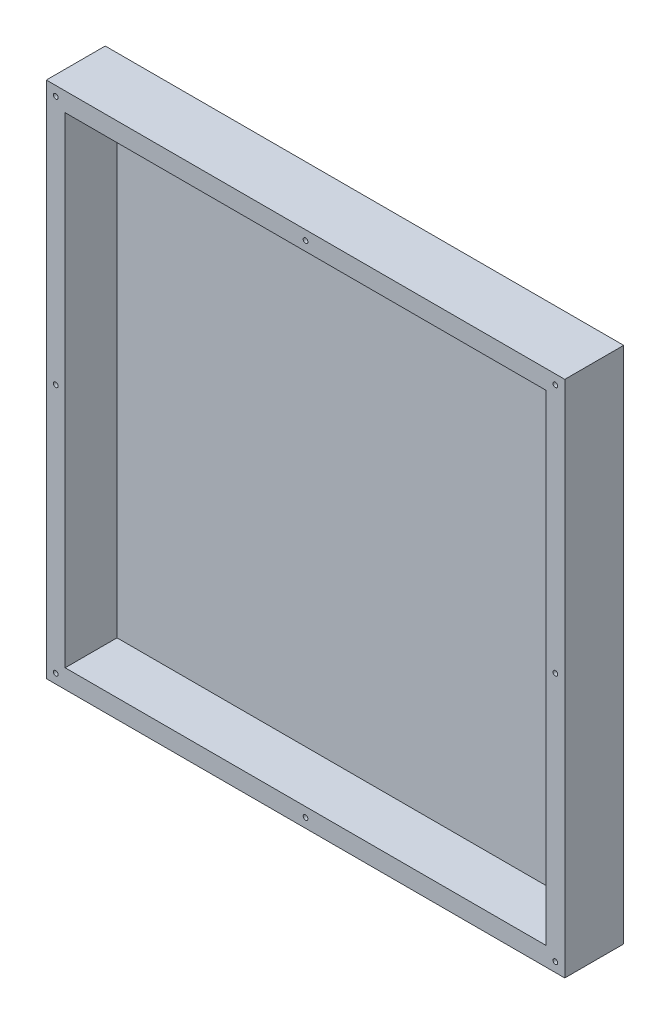
SolidWorks part; units mm, degrees
ref_plane "Front Plane" through (0, 0, 0) normal (0, 0, 1) x (1, 0, 0)
ref_plane "Top Plane" through (0, 0, 0) normal (0, 1, 0) x (1, 0, 0)
ref_plane "Right Plane" through (0, 0, 0) normal (1, 0, 0) x (0, 0, -1)
sketch "Sketch1" plane through (0, 0, 0) normal (0, 0, 1) x (1, 0, 0)
  line L0 (0, 0) -> (220, 0)
  line L1 (55, 0) -> (-55, 0) construction
  line L2 (220, 0) -> (220, 220)
  line L3 (220, 220) -> (0, 220)
  line L4 (0, -55) -> (0, 55) construction
  line L5 (0, 220) -> (0, 0)
extrude "Boss-Extrude1" add sketch "Sketch1" along normal blind 3
sketch "Sketch2" plane through (0, 0, 3) normal (0, 0, 1) x (1, 0, 0)
  line L8 (8, 212) -> (8, 8)
  line L9 (220, 220) -> (0, 220)
  line L10 (220, 220) -> (220, 0)
  line L11 (220, 0) -> (0, 0)
  line L12 (0, 220) -> (0, 0)
  line L13 (212, 8) -> (8, 8)
  line L14 (212, 212) -> (212, 8)
  line L15 (212, 212) -> (8, 212)
  dimension "D1" = 8
extrude "Boss-Extrude3" add sketch "Sketch2" along normal blind 22
sketch "Sketch3" plane through (0, 0, 25) normal (0, 0, 1) x (1, 0, 0)
  line L14 (216, 4) -> (216, 216)
  line L15 (4, 4) -> (216, 4)
  line L16 (4, 216) -> (4, 4)
  line L17 (216, 216) -> (4, 216)
  line L18 (216, 4) -> (216, 216) construction
  line L19 (4, 4) -> (216, 4) construction
  line L20 (4, 216) -> (4, 4) construction
  line L21 (216, 216) -> (4, 216) construction
  circle A0 centre (4, 216) radius 1
  circle A1 centre (110, 216) radius 1
  circle A2 centre (216, 216) radius 1
  circle A3 centre (216, 110) radius 1
  circle A4 centre (216, 4) radius 1
  circle A5 centre (110, 4) radius 1
  circle A6 centre (4, 4) radius 1
  circle A7 centre (4, 110) radius 1
  dimension "D1" = 4
extrude "Cut-Extrude1" cut sketch "Sketch3" against normal through all
